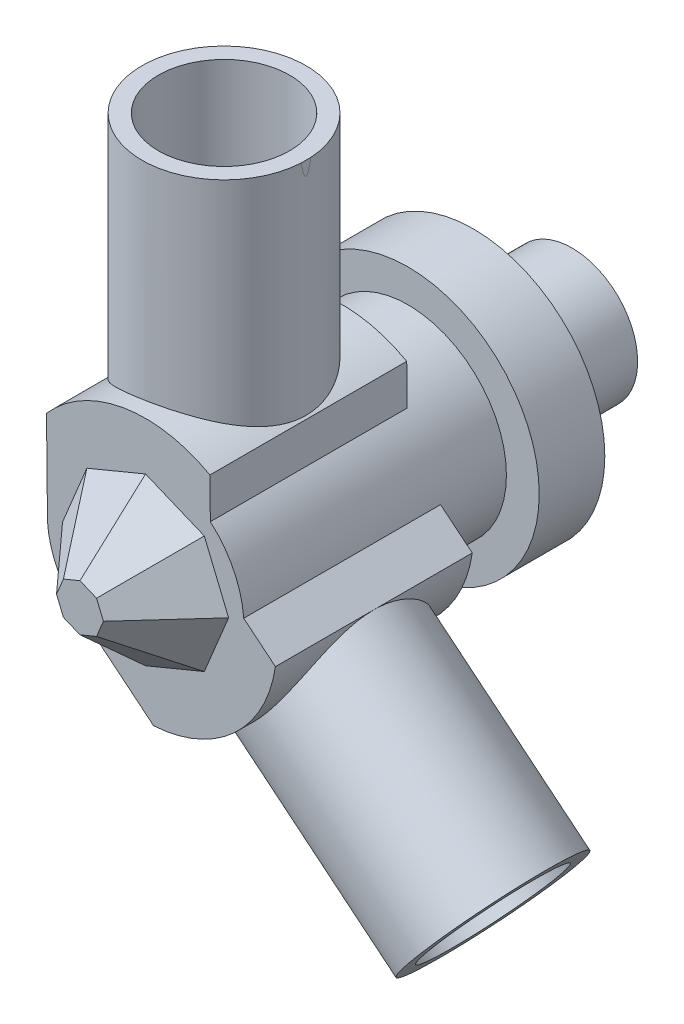
SolidWorks part; units mm, degrees
ref_plane "Front Plane" through (0, 0, 0) normal (0, 0, 1) x (1, 0, 0)
ref_plane "Top Plane" through (0, 0, 0) normal (0, 1, 0) x (1, 0, 0)
ref_plane "Right Plane" through (0, 0, 0) normal (1, 0, 0) x (0, 0, -1)
sketch "Sketch1" plane through (0, 0, 0) normal (0, 0, 1) x (1, 0, 0)
  circle A0 centre (0, 0) radius 25.4
  dimension "D1" = 50.8
extrude "Boss-Extrude1" add sketch "Sketch1" along normal blind 38.1
sketch "Sketch2" plane through (0, 0, 38.1) normal (0, 0, 1) x (1, 0, 0)
  circle A0 centre (0, 0) radius 50.8
  dimension "D1" = 101.6
extrude "Boss-Extrude2" add sketch "Sketch2" along normal blind 25.4
sketch "Sketch3" plane through (0, 0, 63.5) normal (0, 0, 1) x (1, 0, 0)
  circle A0 centre (0, 0) radius 38.1
  dimension "D1" = 76.2
extrude "Boss-Extrude3" add sketch "Sketch3" along normal blind 101.6
sketch "Sketch4" plane through (0, 0, 165.1) normal (0, 0, 1) x (1, 0, 0)
  line L0 (37.9985, 2.7793) -> (116.5319, -61.6805)
  line L1 (116.5319, -61.6805) -> (76.2445, -110.7639)
  line L2 (76.2445, -110.7639) -> (-17.4205, -33.8842)
  line L3 (25.0735, 28.6868) -> (23.9722, 130.2868)
  line L5 (23.9722, 130.2868) -> (-39.4124, 130.2868)
  line L7 (-39.4124, 130.2868) -> (-38.0259, 2.3748)
  circle A0 centre (0, 0) radius 38.1 construction
  circle A1 centre (0, 0) radius 38.1 construction
  arc A2 (-17.4205, -33.8842) -> (37.9985, 2.7793) centre (0, 0) ccw
  arc A3 (25.0735, 28.6868) -> (-38.0259, 2.3748) centre (0, 0) ccw
  dimension "D1" = 101.6
  dimension "D2" = 63.5
  dimension "D3" = 130
  dimension "D4" = 101.6
  dimension "D5" = 121.176
  dimension "D6" = 230
extrude "Boss-Extrude4" add sketch "Sketch4" against normal blind 76.2
sketch "Sketch5" plane through (0, 130.2868, 0) normal (0, 1, 0) x (1, 0, 0)
  line L8 (-41.9524, -167.64) -> (26.5122, -167.64)
  line L9 (26.5122, -167.64) -> (26.5122, -86.36)
  line L10 (26.5122, -86.36) -> (-41.9524, -86.36)
  line L11 (-41.9524, -86.36) -> (-41.9524, -167.64)
  line L12 (-41.9524, -167.64) -> (26.5122, -167.64)
  line L13 (26.5122, -167.64) -> (26.5122, -86.36)
  line L14 (26.5122, -86.36) -> (-41.9524, -86.36)
  line L15 (-41.9524, -86.36) -> (-41.9524, -167.64)
  circle A0 centre (-7.7201, -127) radius 31.75
  dimension "D1" = 63.5
  dimension "D2" = 2.54
extrude "Cut-Extrude1" cut sketch "Sketch5" against normal up to surface (80.0768 mm away)
sketch "Sketch6" plane through (99.8737, -81.9758, 0) normal (0.773, -0.6344, 0) x (0, 0, -1)
  line L8 (-167.64, 28.7963) -> (-167.64, -39.7837)
  line L9 (-167.64, -39.7837) -> (-86.36, -39.7837)
  line L10 (-86.36, -39.7837) -> (-86.36, 28.7963)
  line L11 (-86.36, 28.7963) -> (-167.64, 28.7963)
  line L12 (-167.64, 28.7963) -> (-167.64, -39.7837)
  line L13 (-167.64, -39.7837) -> (-86.36, -39.7837)
  line L14 (-86.36, -39.7837) -> (-86.36, 28.7963)
  line L15 (-86.36, 28.7963) -> (-167.64, 28.7963)
  circle A0 centre (-127, -5.4937) radius 31.75
  dimension "D1" = 63.5
  dimension "D2" = 2.54
extrude "Cut-Extrude2" cut sketch "Sketch6" against normal up to surface (85.7198 mm away)
sketch "Sketch7" plane through (99.8737, -81.9758, 0) normal (0.773, -0.6344, 0) x (0, 0, -1)
  circle A0 centre (-127, -5.4937) radius 25.4
  dimension "D1" = 50.8
extrude "Cut-Extrude3" cut sketch "Sketch7" against normal blind 76.2
sketch "Sketch8" plane through (0, 130.2868, 0) normal (0, 1, 0) x (1, 0, 0)
  circle A0 centre (-7.7201, -127) radius 25.4
  dimension "D1" = 50.8
extrude "Cut-Extrude4" cut sketch "Sketch8" against normal blind 76.2
sketch "Sketch10" plane through (0, 0, 165.1) normal (0, 0, 1) x (1, 0, 0)
  line L0 (32.1449, 0) -> (22.7299, 22.7299)
  line L1 (0, 32.1449) -> (-22.7299, 22.7299)
  line L2 (-22.7299, 22.7299) -> (-32.1449, 0)
  line L3 (-32.1449, 0) -> (-22.7299, -22.7299)
  line L4 (-22.7299, -22.7299) -> (0, -32.1449)
  line L5 (0, -32.1449) -> (22.7299, -22.7299)
  line L6 (22.7299, -22.7299) -> (32.1449, 0)
  line L7 (22.7299, 22.7299) -> (0, 32.1449)
  circle A0 centre (0, 0) radius 29.698 construction
extrude "Boss-Extrude5" add sketch "Sketch10" along normal blind 25.4 draft 40
